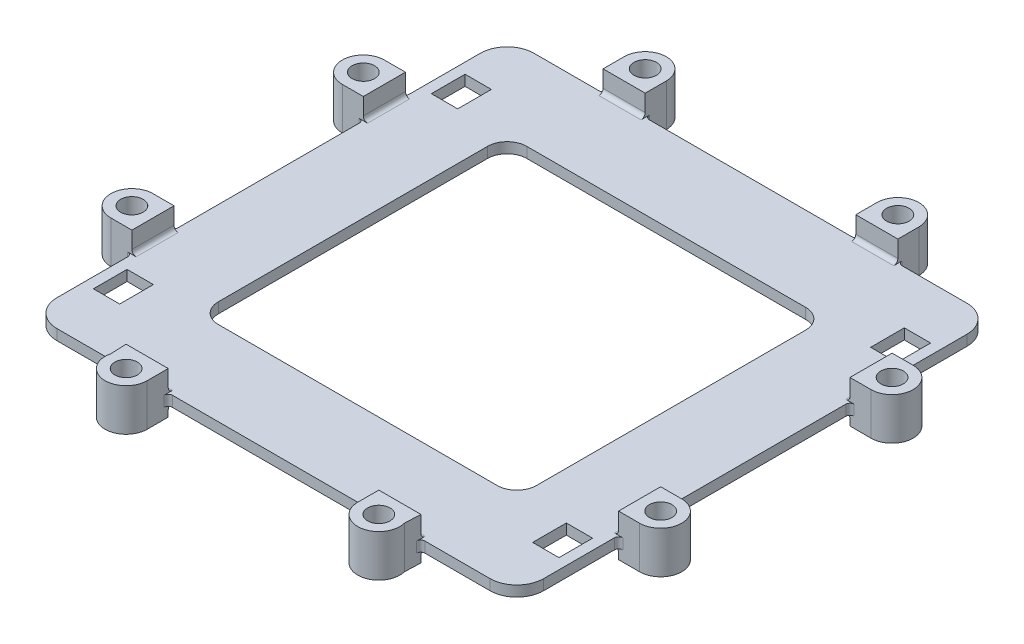
SolidWorks part; units mm, degrees
other "Markup1"
sketch "Sketch2" plane through (0, 2.54, -135.7376) normal (0, 1, 0) x (1, 0, 0)
ref_plane "Front Plane" through (0, 0, 0) normal (0, 0, 1) x (1, 0, 0)
ref_plane "Top Plane" through (0, 0, 0) normal (0, 1, 0) x (1, 0, 0)
ref_plane "Right Plane" through (0, 0, 0) normal (1, 0, 0) x (0, 0, -1)
sketch "Sketch1" plane through (0, 0, 0) normal (0, 1, 0) x (1, 0, 0)
  line L0 (0, 0) -> (0, 127.635)
  line L1 (8.1026, 135.7376) -> (138.6586, 135.7376)
  line L2 (146.7612, 127.635) -> (146.7612, 0)
  line L3 (138.6586, -8.1026) -> (8.1026, -8.1026)
  line L4 (25.4, 104.4189) -> (25.4, 23.2161)
  line L5 (31.3187, 110.3376) -> (115.4425, 110.3376)
  line L6 (121.3612, 104.4189) -> (121.3612, 23.2161)
  line L7 (115.4425, 17.2974) -> (31.3187, 17.2974)
  arc A0 (0, 127.635) -> (8.1026, 135.7376) centre (8.1026, 127.635) cw
  arc A1 (138.6586, 135.7376) -> (146.7612, 127.635) centre (138.6586, 127.635) cw
  arc A2 (146.7612, 0) -> (138.6586, -8.1026) centre (138.6586, 0) cw
  arc A3 (8.1026, -8.1026) -> (0, 0) centre (8.1026, 0) cw
  arc A4 (25.4, 104.4189) -> (31.3187, 110.3376) centre (31.3187, 104.4189) cw
  arc A5 (115.4425, 110.3376) -> (121.3612, 104.4189) centre (115.4425, 104.4189) cw
  arc A6 (121.3612, 23.2161) -> (115.4425, 17.2974) centre (115.4425, 23.2161) cw
  arc A7 (31.3187, 17.2974) -> (25.4, 23.2161) centre (31.3187, 23.2161) cw
  dimension "D2" = 8.1026
  dimension "D4" = 8.1026
  dimension "D1" = 127.635
  dimension "D3" = 130.556
  dimension "D5" = 127.635
  dimension "D6" = 25.4
  dimension "D7" = 25.4
  dimension "D8" = 25.4
  dimension "D9" = 25.4
extrude "Boss-Extrude1" add sketch "Sketch1" along normal blind 3.175
sketch "Sketch3" plane through (0, 3.175, 0) normal (0, 1, 0) x (1, 0, 0)
  line L0 (138.6586, 135.7376) -> (8.1026, 135.7376) construction
  line L1 (3.175, 119.8626) -> (11.1125, 119.8626)
  line L2 (3.175, 119.8626) -> (3.175, 109.7026)
  line L3 (3.175, 109.7026) -> (11.1125, 109.7026)
  line L4 (11.1125, 119.8626) -> (11.1125, 109.7026)
  line L5 (0, 127.635) -> (0, 0) construction
  line L6 (73.3806, 135.7376) -> (73.3806, -8.1026) construction
  line L7 (8.1026, -8.1026) -> (138.6586, -8.1026) construction
  line L8 (143.5862, 119.8626) -> (143.5862, 109.7026)
  line L9 (143.5862, 119.8626) -> (135.6487, 119.8626)
  line L10 (135.6487, 119.8626) -> (135.6487, 109.7026)
  line L11 (143.5862, 109.7026) -> (135.6487, 109.7026)
  line L12 (0, 63.8175) -> (146.7612, 63.8175) construction
  line L13 (146.7612, 0) -> (146.7612, 127.635) construction
  line L14 (135.6487, 7.7724) -> (135.6487, 17.9324)
  line L15 (143.5862, 7.7724) -> (135.6487, 7.7724)
  line L16 (143.5862, 7.7724) -> (143.5862, 17.9324)
  line L17 (143.5862, 17.9324) -> (135.6487, 17.9324)
  line L18 (3.175, 7.7724) -> (3.175, 17.9324)
  line L19 (3.175, 7.7724) -> (11.1125, 7.7724)
  line L20 (11.1125, 7.7724) -> (11.1125, 17.9324)
  line L21 (3.175, 17.9324) -> (11.1125, 17.9324)
  dimension "D1" = 7.9375
  dimension "D2" = 10.16
  dimension "D3" = 15.875
  dimension "D4" = 3.175
extrude "Cut-Extrude1" cut sketch "Sketch3" against normal blind 3.175
sketch "Sketch4" plane through (0, 3.175, 0) normal (0, 1, 0) x (1, 0, 0)
  line L0 (111.4806, 135.7376) -> (35.2806, 135.7376) construction
  line L1 (138.6586, 135.7376) -> (8.1026, 135.7376) construction
  line L2 (115.4425, 110.3376) -> (31.3187, 110.3376) construction
  line L3 (28.9306, 135.7376) -> (41.6306, 135.7376)
  line L4 (41.6306, 135.7376) -> (41.6306, 142.0876)
  line L6 (73.3806, 135.7376) -> (73.3806, -8.1026) construction
  line L7 (8.1026, -8.1026) -> (138.6586, -8.1026) construction
  line L8 (0, 63.8175) -> (146.7612, 63.8175) construction
  line L9 (0, 127.635) -> (0, 0) construction
  line L10 (146.7612, 0) -> (146.7612, 127.635) construction
  line L11 (41.6306, -8.1026) -> (41.6306, -14.4526)
  line L12 (28.9306, -8.1026) -> (29.1202, -12.9125)
  line L13 (28.9306, -8.1026) -> (41.6306, -8.1026)
  line L14 (117.8306, -8.1026) -> (117.641, -12.9125)
  line L15 (105.1306, -8.1026) -> (105.1306, -14.4526)
  line L16 (117.8306, -8.1026) -> (105.1306, -8.1026)
  line L17 (117.8306, 135.7376) -> (117.8306, 142.0876)
  line L18 (105.1306, 135.7376) -> (105.1306, 142.0876)
  line L19 (117.8306, 135.7376) -> (105.1306, 135.7376)
  line L20 (146.7612, 22.5124) -> (146.7612, 98.7124)
  line L21 (146.7612, 92.3624) -> (146.7612, 105.0624)
  line L22 (146.7612, 105.0624) -> (153.1112, 105.0624)
  line L23 (153.1112, 92.3624) -> (146.7612, 92.3624)
  line L24 (146.7612, 22.5726) -> (153.1112, 22.5726)
  line L25 (146.7612, 35.2726) -> (146.7612, 22.5726)
  line L26 (153.1112, 35.2726) -> (146.7612, 35.2726)
  line L27 (-6.35, 35.2726) -> (0, 35.2726)
  line L28 (0, 35.2726) -> (0, 22.5726)
  line L29 (0, 22.5726) -> (-6.35, 22.5726)
  line L30 (0, 92.3624) -> (0, 105.0624)
  line L31 (0, 105.0624) -> (-6.35, 105.0624)
  line L32 (-6.35, 92.3624) -> (0, 92.3624)
  line L33 (28.9306, 135.7376) -> (28.9306, 142.0876)
  circle A1 centre (35.2806, 142.0876) radius 3.3909
  circle A2 centre (35.2806, -14.4526) radius 3.3909
  arc A3 (41.6306, -14.4526) -> (29.1202, -12.9125) centre (35.2806, -14.4526) cw
  arc A4 (105.1306, -14.4526) -> (117.641, -12.9125) centre (111.4806, -14.4526) ccw
  circle A5 centre (111.4806, -14.4526) radius 3.3909
  arc A6 (105.1306, 142.0876) -> (117.8306, 142.0876) centre (111.4806, 142.0876) cw
  circle A7 centre (111.4806, 142.0876) radius 3.3909
  arc A8 (153.1112, 105.0624) -> (153.1112, 92.3624) centre (153.1112, 98.7124) cw
  circle A9 centre (153.1112, 98.7124) radius 3.3909
  circle A10 centre (153.1112, 28.9226) radius 3.3909
  arc A11 (153.1112, 22.5726) -> (153.1112, 35.2726) centre (153.1112, 28.9226) ccw
  circle A12 centre (-6.35, 28.9226) radius 3.3909
  arc A13 (-6.35, 22.5726) -> (-6.35, 35.2726) centre (-6.35, 28.9226) cw
  arc A15 (-6.35, 105.0624) -> (-6.35, 92.3624) centre (-6.35, 98.7124) ccw
  arc A16 (28.9306, 142.0876) -> (41.6306, 142.0876) centre (35.2806, 142.0876) cw
  circle A17 centre (-6.35, 98.7124) radius 3.3909
  point P5 (73.3806, 135.7376)
  point P7 (73.3806, 110.3376)
  point P11 (35.2806, 135.7376)
  point P46 (146.7612, 60.6124)
  point P49 (146.7612, 98.7124)
  dimension "D2" = 6.7818
  dimension "D7" = 6.35
  dimension "D10" = 6.35
  dimension "D11" = 6.35
  dimension "D8" = 6.35
  dimension "D1" = 76.2
  dimension "D3" = 12.7
  dimension "D4" = 76.2
  dimension "D5" = 12.7
  dimension "D9" = 6.35
extrude "Boss-Extrude2" add sketch "Sketch4" along normal mid plane 12.7 contours A2 | A13 L27 L28 L29 | A12 | A3 L12 L13 L11 | A4 L14 L16 L15 | A5 | L24 A11 L26 L25 | A10 | A9 | A8 L23 L21 L22 | A7 | L18 A6 L17 L19 | A1 | L4 A16 L33 L3 | A17 | A15 L32 L30 L31
fillet "Fillet1" radius 1.27 2 edges at (41.6306, 1.5875, 8.1026) (28.9306, 1.5875, 8.1026)
fillet "Fillet2" radius 1.27 2 edges at (35.2806, 0, 8.1026) (35.2806, 3.175, 8.1026)
fillet "Fillet3" radius 1.27 14 edges at (111.4806, 0, 8.1026) (111.4806, 3.175, 8.1026) (146.7612, 3.175, -28.9226) (146.7612, 0, -28.9226) (146.7612, 0, -98.7124) (146.7612, 3.175, -98.7124) (111.4806, 3.175, -135.7376) (111.4806, 0, -135.7376) (35.2806, 0, -135.7376) (0, 0, -98.7124) (35.2806, 3.175, -135.7376) (0, 3.175, -98.7124) (0, 0, -28.9226) (0, 3.175, -28.9226)
fillet "Fillet4" radius 1.27 14 edges at (0, 1.5875, -92.3624) (0, 1.5875, -105.0624) (0, 1.5875, -35.2726) (0, 1.5875, -22.5726) (117.8306, 1.5875, 8.1026) (105.1306, 1.5875, 8.1026) (146.7612, 1.5875, -35.2726) (146.7612, 1.5875, -22.5726) (146.7612, 1.5875, -92.3624) (146.7612, 1.5875, -105.0624) (117.8306, 1.5875, -135.7376) (105.1306, 1.5875, -135.7376) (28.9306, 1.5875, -135.7376) (41.6306, 1.5875, -135.7376)
